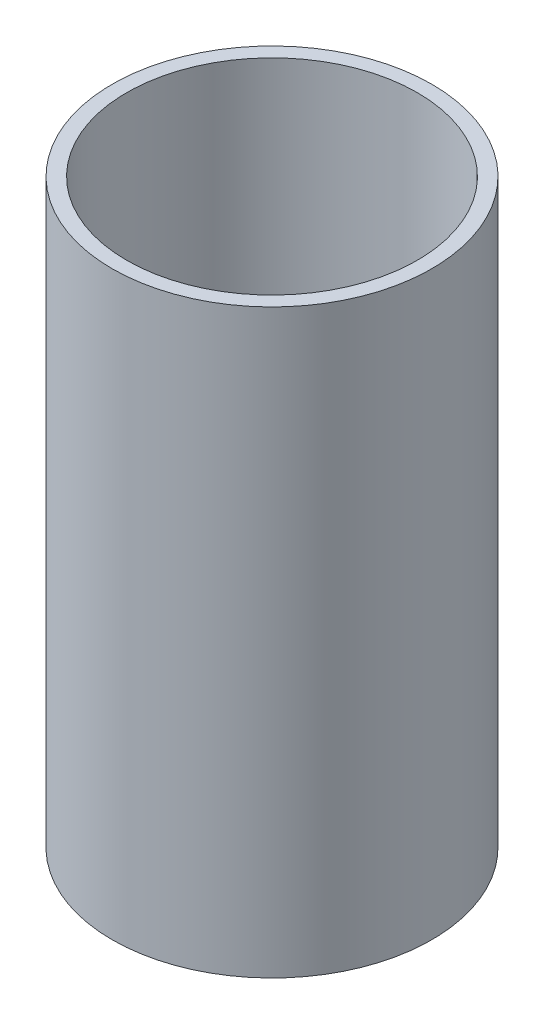
SolidWorks part; units mm, degrees
material "Pure Lead"
ref_plane "Front Plane" through (0, 0, 0) normal (0, 0, 1) x (1, 0, 0)
ref_plane "Top Plane" through (0, 0, 0) normal (0, 1, 0) x (1, 0, 0)
ref_plane "Right Plane" through (0, 0, 0) normal (1, 0, 0) x (0, 0, -1)
sketch "Sketch1" plane through (0, 0, 0) normal (0, 1, 0) x (1, 0, 0)
  circle A0 centre (0, 0) radius 25.4
  circle A1 centre (0, 0) radius 27.94
  dimension "D1" = 50.8
  dimension "D2" = 55.88
extrude "Extrude1" add sketch "Sketch1" along normal blind 101.6
